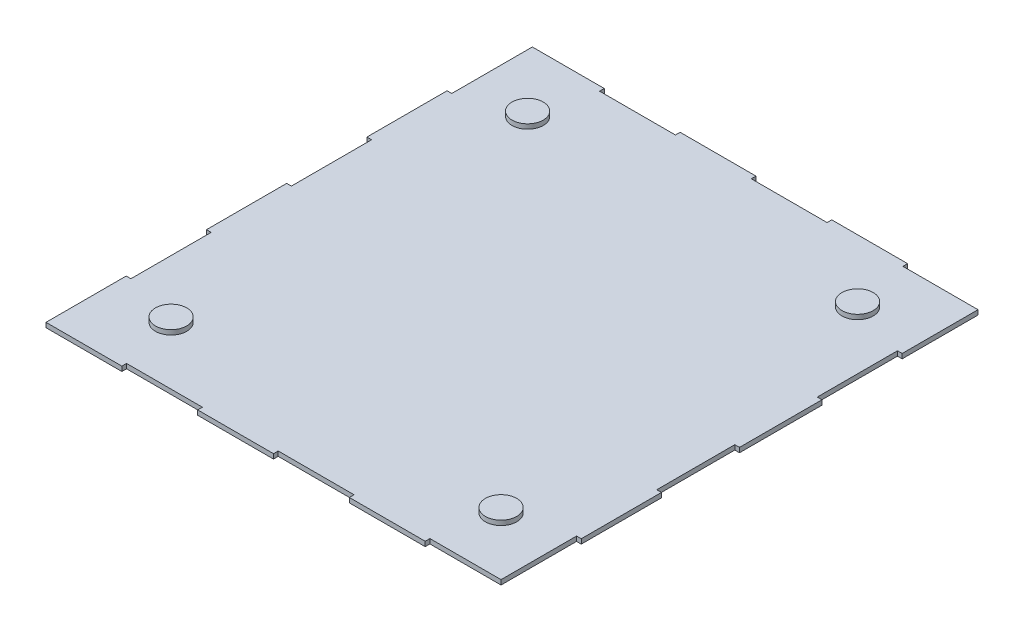
SolidWorks part; units mm, degrees
ref_plane "Спереди" through (0, 0, 0) normal (0, 0, 1) x (1, 0, 0)
ref_plane "Сверху" through (0, 0, 0) normal (0, 1, 0) x (1, 0, 0)
ref_plane "Справа" through (0, 0, 0) normal (1, 0, 0) x (0, 0, -1)
other "Configuration Table"
sketch "Эскиз1" plane through (0, 0, 0) normal (0, 1, 0) x (1, 0, 0)
  line L0 (-130.8112, 121.6694) -> (-84.8112, 121.6694)
  line L1 (-133.8112, 70.1694) -> (-133.8112, 18.8694)
  line L2 (-133.8112, -186.3306) -> (-85.3112, -186.3306)
  line L3 (157.1888, 118.6694) -> (157.1888, 70.1694)
  line L4 (-130.8112, 121.6694) -> (-130.8112, 70.1694)
  line L5 (-130.8112, 70.1694) -> (-133.8112, 70.1694)
  line L6 (-130.8112, 18.8694) -> (-133.8112, 18.8694)
  line L7 (-130.8112, 18.8694) -> (-130.8112, -32.4306)
  line L8 (-130.8112, -32.4306) -> (-133.8112, -32.4306)
  line L9 (-130.8112, -83.7306) -> (-133.8112, -83.7306)
  line L10 (-130.8112, -83.7306) -> (-130.8112, -135.0306)
  line L11 (-130.8112, -135.0306) -> (-133.8112, -135.0306)
  line L12 (-84.8112, 121.6694) -> (-84.8112, 118.6694)
  line L13 (-84.8112, 118.6694) -> (-36.3112, 118.6694)
  line L14 (-36.3112, 121.6694) -> (-36.3112, 118.6694)
  line L15 (12.1888, 121.6694) -> (12.1888, 118.6694)
  line L16 (12.1888, 118.6694) -> (60.6888, 118.6694)
  line L17 (60.6888, 121.6694) -> (60.6888, 118.6694)
  line L18 (-36.3112, 121.6694) -> (12.1888, 121.6694)
  line L19 (109.1888, 121.6694) -> (109.1888, 118.6694)
  line L20 (109.1888, 118.6694) -> (157.1888, 118.6694)
  line L21 (157.1888, 70.1694) -> (154.1888, 70.1694)
  line L22 (157.1888, 18.8694) -> (154.1888, 18.8694)
  line L23 (154.1888, 70.1694) -> (154.1888, 18.8694)
  line L24 (157.1888, -33.8306) -> (154.1888, -33.8306)
  line L25 (157.1888, -83.7306) -> (154.1888, -83.7306)
  line L26 (154.1888, -33.8306) -> (154.1888, -83.7306)
  line L27 (157.1888, -135.0306) -> (154.1888, -135.0306)
  line L28 (154.1888, -135.0306) -> (154.1888, -183.3306)
  line L29 (60.6888, 121.6694) -> (109.1888, 121.6694)
  line L30 (157.1888, 18.8694) -> (157.1888, -33.8306)
  line L31 (157.1888, -83.7306) -> (157.1888, -135.0306)
  line L32 (-133.8112, -135.0306) -> (-133.8112, -186.3306)
  line L33 (-133.8112, -32.4306) -> (-133.8112, -83.7306)
  line L34 (60.1888, -186.3306) -> (108.6888, -186.3306)
  line L36 (-85.3112, -186.3306) -> (-85.3112, -183.3306)
  line L37 (-85.3112, -183.3306) -> (-36.8112, -183.3306)
  line L38 (-36.8112, -186.3306) -> (-36.8112, -183.3306)
  line L40 (11.6888, -186.3306) -> (11.6888, -183.3306)
  line L41 (11.6888, -183.3306) -> (60.1888, -183.3306)
  line L42 (60.1888, -186.3306) -> (60.1888, -183.3306)
  line L44 (108.6888, -186.3306) -> (108.6888, -183.3306)
  line L45 (108.6888, -183.3306) -> (154.1888, -183.3306)
  line L47 (-36.8112, -186.3306) -> (11.6888, -186.3306)
  dimension "D1" = 3
  dimension "D2" = 308
  dimension "D3" = 291
  dimension "D4" = 51.5
  dimension "D5" = 3
  dimension "D6" = 51.3
  dimension "D7" = 51.3
  dimension "D8" = 51.3
  dimension "D9" = 51.3
  dimension "D10" = 48.5
  dimension "D11" = 48.5
  dimension "D12" = 46
  dimension "D13" = 48.5
  dimension "D14" = 48.5
  dimension "D15" = 3
  dimension "D16" = 48.5
  dimension "D17" = 48.5
  dimension "D18" = 3
  dimension "D19" = 48.5
  dimension "D20" = 48.5
  dimension "D21" = 48.5
extrude "Бобышка-Вытянуть1" add sketch "Эскиз1" along normal blind 3
sketch "Эскиз2" plane through (0, 0, 0) normal (0, -1, 0) x (1, 0, 0)
  line L0 (-133.8112, 135.0306) -> (-133.8112, 186.3306) construction
  line L1 (-93.8112, 146.3306) -> (117.1888, 146.3306) construction
  line L2 (-93.8112, 146.3306) -> (-93.8112, -81.6694) construction
  line L3 (-93.8112, -81.6694) -> (117.1888, -81.6694) construction
  line L4 (117.1888, 146.3306) -> (117.1888, -81.6694) construction
  line L5 (157.1888, 135.0306) -> (157.1888, 83.7306) construction
  line L6 (-133.8112, 186.3306) -> (-85.3112, 186.3306) construction
  line L7 (109.1888, -121.6694) -> (60.6888, -121.6694) construction
  circle A0 centre (-93.8112, 146.3306) radius 10
  circle A1 centre (117.1888, 146.3306) radius 10
  circle A2 centre (117.1888, -81.6694) radius 10
  circle A3 centre (-93.8112, -81.6694) radius 10
  dimension "D5" = 20
  dimension "D1" = 40
  dimension "D2" = 40
  dimension "D3" = 40
  dimension "D4" = 40
extrude "Бобышка-Вытянуть3" add sketch "Эскиз2" against normal blind 6
